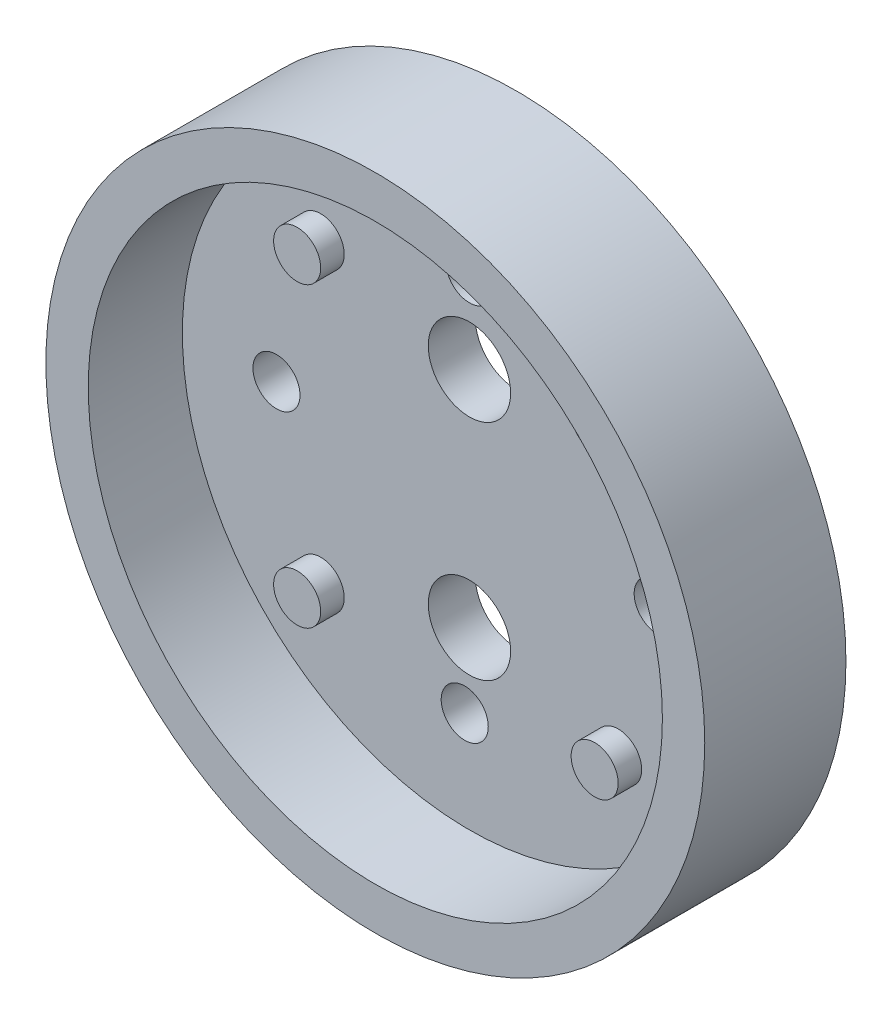
SolidWorks part; units mm, degrees
ref_plane "Front Plane" through (0, 0, 0) normal (0, 0, 1) x (1, 0, 0)
ref_plane "Top Plane" through (0, 0, 0) normal (0, 1, 0) x (1, 0, 0)
ref_plane "Right Plane" through (0, 0, 0) normal (1, 0, 0) x (0, 0, -1)
sketch "Sketch1" plane through (0, 0, 0) normal (0, 0, 1) x (1, 0, 0)
  circle A0 centre (0, 0) radius 14
  dimension "D1" = 28
extrude "Boss-Extrude1" add sketch "Sketch1" along normal blind 2
sketch "Sketch2" plane through (0, 0, 2) normal (0, 0, 1) x (1, 0, 0)
  circle A0 centre (0, 0) radius 14
  circle A1 centre (0, 0) radius 12.2
  circle A2 centre (0, 0) radius 14 construction
  dimension "D1" = 1.8
extrude "Boss-Extrude2" add sketch "Sketch2" along normal blind 4
sketch "Sketch3" plane through (0, 0, 2) normal (0, 0, 1) x (1, 0, 0)
  line L0 (0, 12.2) -> (0, -12.2) construction
  line L1 (12.2, 0) -> (-12.2, 0) construction
  line L2 (0.8321, 9.2) -> (-1.8969, 9.2) construction
  line L3 (0, 12.2) -> (-3.3981, 12.2) construction
  circle A0 centre (0, 0) radius 12.2 construction
  circle A1 centre (0, 8.2) radius 1
  circle A2 centre (8, 0) radius 1
  circle A3 centre (-0.2, -8) radius 1
  circle A4 centre (-8.2, 0.2) radius 1
  dimension "D1" = 2
  dimension "D2" = 3
  dimension "D3" = 4
extrude "Cut-Extrude1" cut sketch "Sketch3" against normal through all
sketch "Sketch4" plane through (0, 0, 2) normal (0, 0, 1) x (1, 0, 0)
  line L0 (0, 3) -> (0, 0) construction
  line L1 (0, 0) -> (0, -3) construction
  circle A0 centre (0, 4.75) radius 1.75
  circle A1 centre (0, -4.75) radius 1.75
  dimension "D1" = 3.5
  dimension "D2" = 3
extrude "Cut-Extrude2" cut sketch "Sketch4" against normal through all
sketch "Sketch5" plane through (0, 0, 2) normal (0, 0, 1) x (1, 0, 0)
  line L0 (0, 0) -> (-8.6267, -8.6267) construction
  line L1 (0, 0) -> (-12.2, 0) construction
  circle A0 centre (0, 0) radius 12.2 construction
  circle A1 centre (0, 0) radius 12.2 construction
  circle A2 centre (-6.3208, -6.3208) radius 1
  circle A3 centre (-6.3208, 6.3208) radius 1
  circle A4 centre (6.3208, 6.3208) radius 1
  circle A5 centre (6.3208, -6.3208) radius 1
  dimension "D2" = 4
  dimension "D1" = 45
extrude "Boss-Extrude3" add sketch "Sketch5" along normal blind 1
